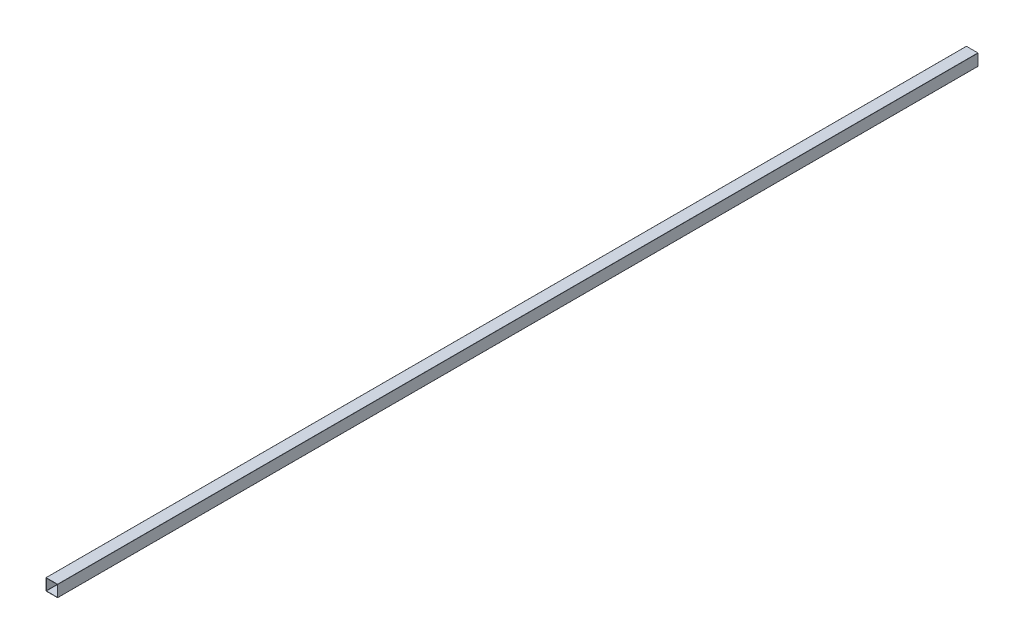
SolidWorks part; units mm, degrees
material "AISI 1035 Acero (SS)"
ref_plane "Alzado" through (0, 0, 0) normal (0, 0, 1) x (1, 0, 0)
ref_plane "Planta" through (0, 0, 0) normal (0, 1, 0) x (1, 0, 0)
ref_plane "Vista lateral" through (0, 0, 0) normal (1, 0, 0) x (0, 0, -1)
sketch "Croquis1" plane through (0, 0, 0) normal (0, 0, 1) x (1, 0, 0)
  line L0 (-36.21, -36.21) -> (-36.21, 36.21)
  line L1 (-38.1, -38.1) -> (38.1, -38.1)
  line L2 (-38.1, -38.1) -> (-38.1, 38.1)
  line L3 (-38.1, 38.1) -> (38.1, 38.1)
  line L4 (38.1, -38.1) -> (38.1, 38.1)
  line L5 (-38.1, -38.1) -> (38.1, 38.1) construction
  line L6 (-38.1, 38.1) -> (38.1, -38.1) construction
  line L7 (-36.21, 36.21) -> (36.21, 36.21)
  line L8 (36.21, -36.21) -> (36.21, 36.21)
  line L9 (-36.21, -36.21) -> (36.21, -36.21)
  point P0 (0, 0)
  dimension "D1" = 76.2
  dimension "D3" = 1.89
extrude "Saliente-Extruir1" add sketch "Croquis1" against normal blind 6000
fillet "Redondeo1" radius 1 8 edges at (-36.21, 36.21, -3000) (36.21, 36.21, -3000) (36.21, -36.21, -3000) (-38.1, -38.1, -3000) (-38.1, 38.1, -3000) (-36.21, -36.21, -3000) (38.1, -38.1, -3000) (38.1, 38.1, -3000)
